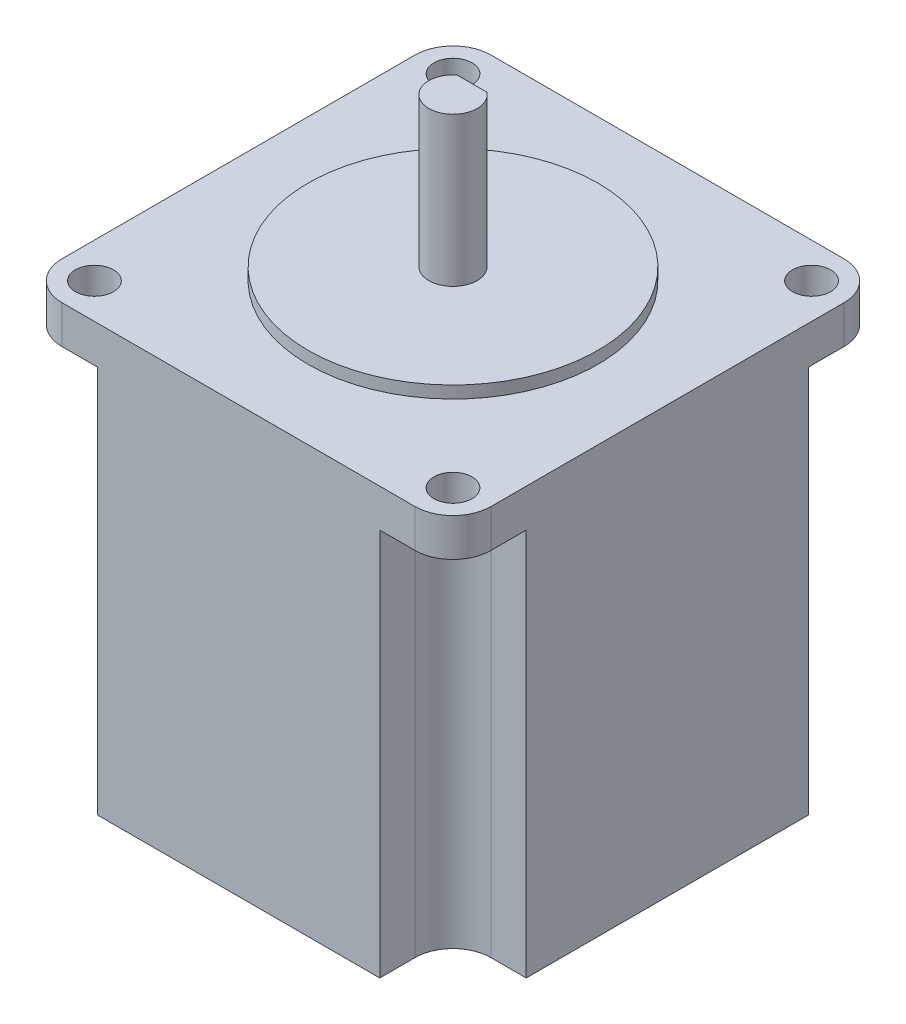
SolidWorks part; units mm, degrees
ref_plane "Front Plane" through (0, 0, 0) normal (0, 0, 1) x (1, 0, 0)
ref_plane "Top Plane" through (0, 0, 0) normal (0, 1, 0) x (1, 0, 0)
ref_plane "Right Plane" through (0, 0, 0) normal (1, 0, 0) x (0, 0, -1)
sketch "Sketch1" plane through (0, 0, 0) normal (0, 1, 0) x (1, 0, 0)
  line L1 (-28.2, -28.2) -> (28.2, -28.2)
  line L2 (-28.2, -28.2) -> (-28.2, 28.2)
  line L3 (-28.2, 28.2) -> (28.2, 28.2)
  line L4 (28.2, -28.2) -> (28.2, 28.2)
  line L5 (-28.2, -28.2) -> (28.2, 28.2) construction
  line L6 (-28.2, 28.2) -> (28.2, -28.2) construction
  point P0 (0, 0)
  dimension "D1" = 56.4
  dimension "D2" = 56.4
extrude "Boss-Extrude1" add sketch "Sketch1" along normal blind 56
sketch "Sketch2" plane through (0, 56, 0) normal (0, 1, 0) x (1, 0, 0)
  line L1 (-23.57, -23.57) -> (23.57, -23.57) construction
  line L2 (-23.57, -23.57) -> (-23.57, 23.57) construction
  line L3 (-23.57, 23.57) -> (23.57, 23.57) construction
  line L4 (23.57, -23.57) -> (23.57, 23.57) construction
  line L5 (-23.57, -23.57) -> (23.57, 23.57) construction
  line L6 (-23.57, 23.57) -> (23.57, -23.57) construction
  circle A0 centre (-23.57, 23.57) radius 2.5
  circle A1 centre (23.57, 23.57) radius 2.5
  circle A2 centre (23.57, -23.57) radius 2.5
  circle A3 centre (-23.57, -23.57) radius 2.5
  point P0 (0, 0)
  point P16 (0, 0)
  dimension "D3" = 5
  dimension "D1" = 47.14
  dimension "D2" = 47.14
  dimension "D4" = 4
extrude "Cut-Extrude1" cut sketch "Sketch2" against normal blind 56
sketch "Sketch4" plane through (0, 0, 0) normal (0, -1, 0) x (1, 0, 0)
  line L0 (-18.57, 23.57) -> (-18.57, 28.2)
  line L1 (-23.57, 18.57) -> (-28.2, 18.57)
  line L2 (23.57, 18.57) -> (28.2, 18.57)
  line L3 (18.57, 23.57) -> (18.57, 28.2)
  line L4 (18.57, -23.57) -> (18.57, -28.2)
  line L5 (-18.57, 28.2) -> (18.57, 28.2) construction
  line L6 (-28.2, 28.2) -> (28.2, 28.2) construction
  line L7 (28.2, -18.57) -> (28.2, 18.57) construction
  line L8 (28.2, 28.2) -> (28.2, -28.2) construction
  line L9 (-18.57, -28.2) -> (18.57, -28.2) construction
  line L10 (28.2, -28.2) -> (-28.2, -28.2) construction
  line L11 (-28.2, -18.57) -> (-28.2, 18.57) construction
  line L12 (-28.2, -28.2) -> (-28.2, 28.2) construction
  line L13 (0, -28.2) -> (0, 28.2) construction
  line L14 (-28.2, 0) -> (28.2, 0) construction
  line L15 (23.57, -18.57) -> (28.2, -18.57)
  line L16 (-23.57, -18.57) -> (-28.2, -18.57)
  line L17 (-18.57, -23.57) -> (-18.57, -28.2)
  line L18 (-28.2, 18.57) -> (-28.2, 28.2)
  line L19 (-28.2, 28.2) -> (-18.57, 28.2)
  line L20 (18.57, 28.2) -> (28.2, 28.2)
  line L21 (28.2, 28.2) -> (28.2, 18.57)
  line L22 (28.2, -18.57) -> (28.2, -28.2)
  line L23 (28.2, -28.2) -> (18.57, -28.2)
  line L24 (-18.57, -28.2) -> (-28.2, -28.2)
  line L25 (-28.2, -28.2) -> (-28.2, -18.57)
  arc A0 (-23.57, 18.57) -> (-18.57, 23.57) centre (-23.57, 23.57) ccw
  arc A1 (18.57, 23.57) -> (23.57, 18.57) centre (23.57, 23.57) ccw
  arc A2 (23.57, -18.57) -> (18.57, -23.57) centre (23.57, -23.57) ccw
  arc A3 (-18.57, -23.57) -> (-23.57, -18.57) centre (-23.57, -23.57) ccw
  point P5 (0, 28.2)
  point P10 (28.2, 0)
  point P17 (0, -28.2)
  point P22 (-28.2, 0)
  point P26 (0, 0)
  point P30 (0, 0)
  point P49 (0, 0)
  dimension "D2" = 4
  dimension "D1" = 10
extrude "Cut-Extrude2" cut sketch "Sketch4" against normal blind 51
fillet "Fillet1" radius 5 4 edges at (28.2, 53.5, -28.2) (-28.2, 53.5, -28.2) (28.2, 53.5, 28.2) (-28.2, 53.5, 28.2)
sketch "Sketch5" plane through (0, 56, 0) normal (0, 1, 0) x (1, 0, 0)
  circle A0 centre (0, 0) radius 19.05
  dimension "D1" = 38.1
extrude "Boss-Extrude2" add sketch "Sketch5" along normal blind 1.6
sketch "Sketch6" plane through (0, 57.6, 0) normal (0, 1, 0) x (1, 0, 0)
  circle A0 centre (0, 0) radius 3.175
  dimension "D1" = 6.35
extrude "Boss-Extrude3" add sketch "Sketch6" along normal blind 19.6
sketch "Sketch7" plane through (0, 77.2, 0) normal (0, 1, 0) x (1, 0, 0)
  line L0 (0, -3.175) -> (0, 2.495) construction
  line L1 (-1.9636, 2.495) -> (1.9636, 2.495)
  line L2 (-3.9742, 2.495) -> (-1.9636, 2.495) construction
  arc A1 (-1.9636, 2.495) -> (0, -3.175) centre (0, 0) ccw construction
  circle A2 centre (0, 0) radius 3.175
  arc A3 (1.9636, 2.495) -> (-1.9636, 2.495) centre (0, 0) ccw
  arc A4 (0, -3.175) -> (1.9636, 2.495) centre (0, 0) ccw construction
  point P8 (0, 2.495)
  dimension "D2" = 5.67
  dimension "D1" = 0
extrude "Cut-Extrude3" cut sketch "Sketch7" against normal blind 17
